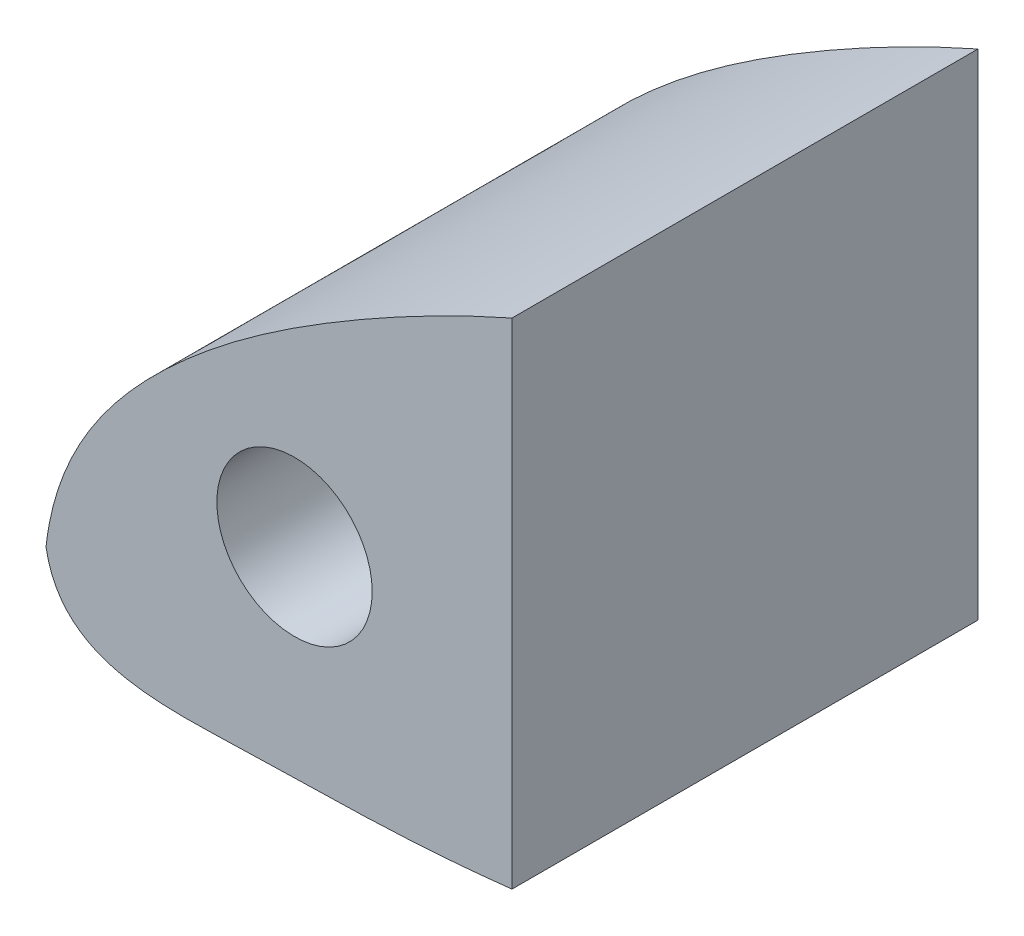
SolidWorks part; units mm, degrees
ref_plane "Front Plane" through (0, 0, 0) normal (0, 0, 1) x (1, 0, 0)
ref_plane "Top Plane" through (0, 0, 0) normal (0, 1, 0) x (1, 0, 0)
ref_plane "Right Plane" through (0, 0, 0) normal (1, 0, 0) x (0, 0, -1)
sketch "Sketch1" plane through (0, 0, 0) normal (0, 0, 1) x (1, 0, 0)
  spline S0 degree 3 poles (0.0006, 0.0001) (0.8106, 7.3592) (8.6491, 17.8566) (26.2867, 29.9752) (52.1111, 42.0692) (89.5976, 49.2908) (131.4008, 47.8848) (173.2567, 40.0411) (217.9611, 29.613) (256.9521, 19.5289) (290.3598, 8.711) (301.2732, 4.3828) (314.8169, -0.5162) (309.8463, 0.0001) knots 0 0 0 0 0.060864 0.113688 0.188609 0.312909 0.448482 0.557612 0.691544 0.852438 0.929756 0.976058 1 1 1 1
  spline S1 degree 3 poles (309.8463, 0.0001) (303.9568, 1.471) (293.9895, 2.094) (276.264, 4.5144) (260.8463, 5.4274) (235.8588, 7.8703) (205.1014, 8.8381) (157.7186, 9.0307) (110.4973, 6.1815) (66.5062, -0.5867) (36.4547, -6.0985) (15.3166, -6.1891) (1.2307, -6.9241) (0.0006, 0.0001) knots 0 0 0 0 0.057787 0.095275 0.171021 0.205339 0.335319 0.464904 0.658702 0.785512 0.893517 0.943092 1 1 1 1
extrude "Boss-Extrude1" add sketch "Sketch1" along normal blind 38.1
sketch "Sketch2" plane through (0, 0, 38.1) normal (0, 0, 1) x (1, 0, 0)
  circle A0 centre (20.32, 10.16) radius 6.35
  circle A1 centre (227.2963, 19.0501) radius 3.175
  dimension "D2" = 12.7
  dimension "D3" = 6.35
  dimension "D6" = 20.32
  dimension "D1" = 82.55
  dimension "D4" = 19.05
  dimension "D5" = 10.16
extrude "Cut-Extrude1" cut sketch "Sketch2" against normal through all
sketch "Sketch3" plane through (0, 0, 38.1) normal (0, 0, 1) x (1, 0, 0)
  line L1 (38.1, 71.718) -> (331.2889, 71.718)
  line L2 (38.1, 71.718) -> (38.1, -66.2532)
  line L3 (38.1, -66.2532) -> (331.2889, -66.2532)
  line L4 (331.2889, 71.718) -> (331.2889, -66.2532)
  dimension "D1" = 38.1
extrude "Cut-Extrude2" cut sketch "Sketch3" against normal through all
